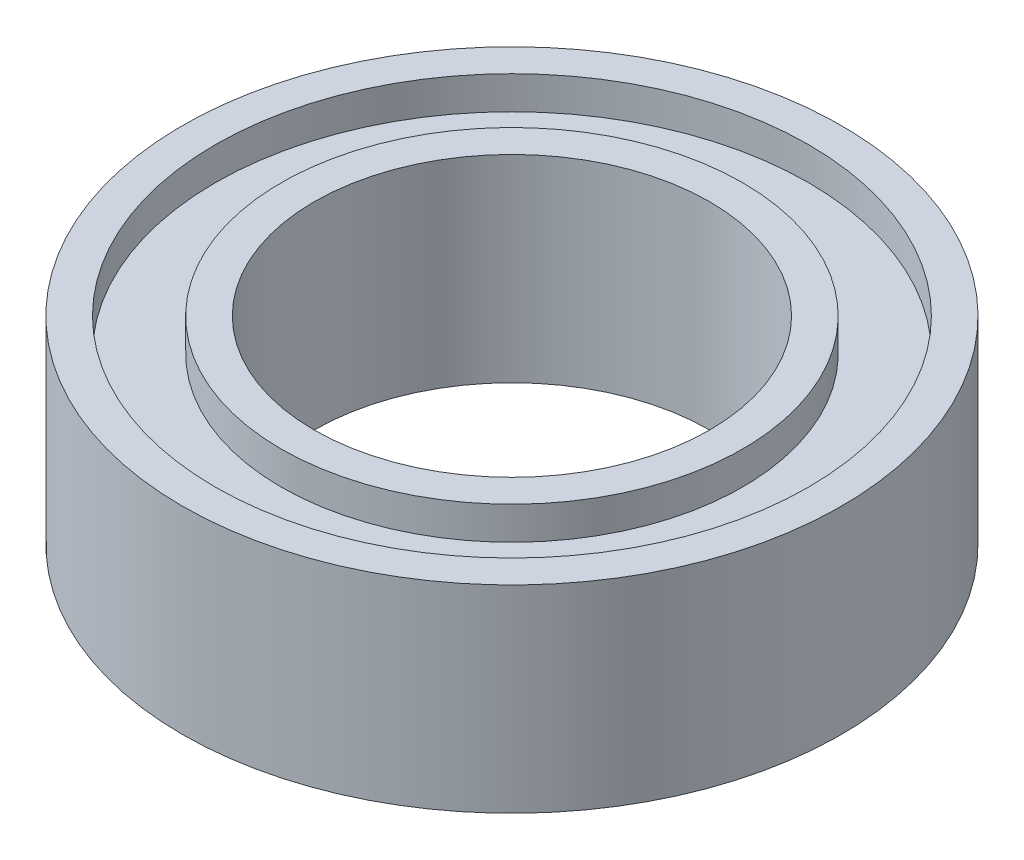
SolidWorks part; units mm, degrees
ref_plane "Front Plane" through (0, 0, 0) normal (0, 0, 1) x (1, 0, 0)
ref_plane "Top Plane" through (0, 0, 0) normal (0, 1, 0) x (1, 0, 0)
ref_plane "Right Plane" through (0, 0, 0) normal (1, 0, 0) x (0, 0, -1)
sketch "Sketch1" plane through (0, 0, 0) normal (0, 1, 0) x (1, 0, 0)
  circle A0 centre (0, 0) radius 5
  circle A1 centre (0, 0) radius 3
  dimension "D1" = 6
  dimension "D2" = 10
extrude "Boss-Extrude1" add sketch "Sketch1" along normal mid plane 3
sketch "Sketch5" plane through (0, 1.5, 0) normal (0, 1, 0) x (1, 0, 0)
  circle A0 centre (0, 0) radius 3.5
  circle A1 centre (0, 0) radius 4.5
  circle A2 centre (0, 0) radius 3 construction
  circle A3 centre (0, 0) radius 5 construction
  dimension "D1" = 0.5
  dimension "D2" = 0.5
extrude "Cut-Extrude1" cut sketch "Sketch5" against normal blind 0.5
mirror "Mirror1" about plane through (0, 0, 0) normal (0, 1, 0) of "Cut-Extrude1"
